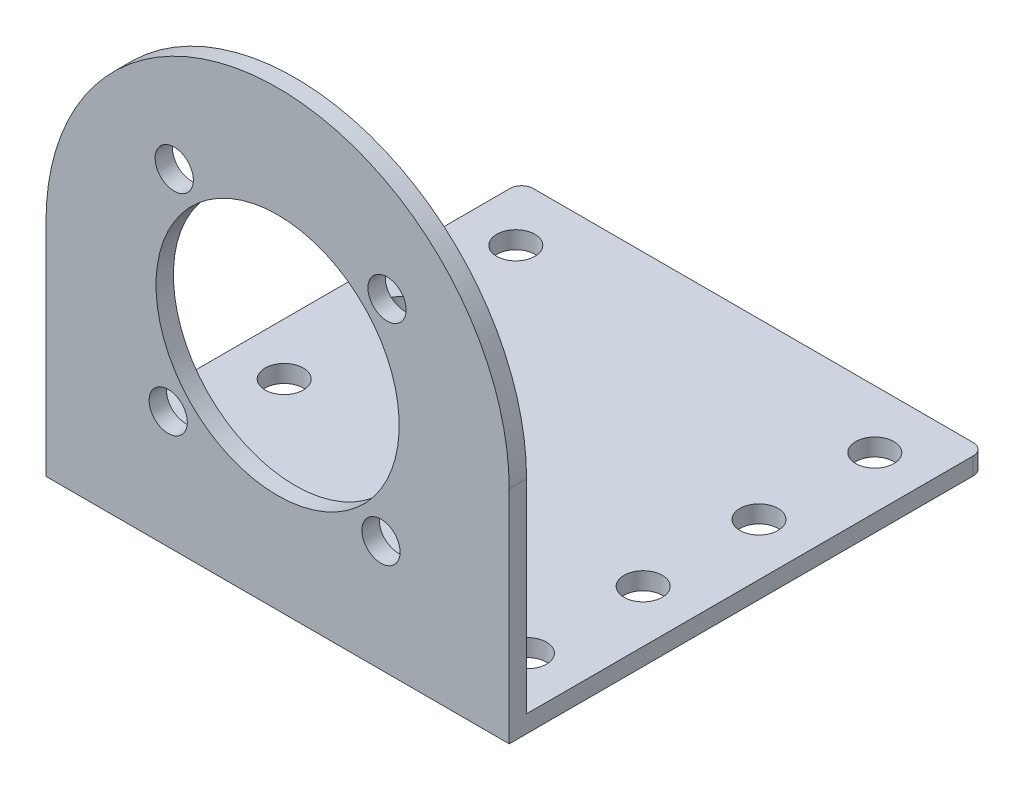
SolidWorks part; units mm, degrees
ref_plane "Front Plane" through (0, 0, 0) normal (0, 0, 1) x (1, 0, 0)
ref_plane "Top Plane" through (0, 0, 0) normal (0, 1, 0) x (1, 0, 0)
ref_plane "Right Plane" through (0, 0, 0) normal (1, 0, 0) x (0, 0, -1)
sketch "Sketch2" plane through (0, 0, 0) normal (1, 0, 0) x (0, 0, -1)
  line L1 (-36.8894, 36.5355) -> (-35.3894, 36.5355)
  line L2 (-36.8894, 36.5355) -> (-36.8894, -2.5345)
  line L3 (-36.8894, -2.5345) -> (-35.3894, -2.5345)
  line L4 (-35.3894, 36.5355) -> (-35.3894, -2.5345)
  line L5 (-36.8894, -2.5345) -> (4.1796, -2.5345)
  line L6 (-36.8894, -2.5345) -> (-36.8894, -1.0345)
  line L7 (-36.8894, -1.0345) -> (4.1796, -1.0345)
  line L8 (4.1796, -2.5345) -> (4.1796, -1.0345)
  dimension "D1" = 1.5
  dimension "D2" = 1.5
  dimension "D3" = 39.07
  dimension "D4" = 41.069
extrude "Boss-Extrude1" add sketch "Sketch2" along normal blind 40 contours L3 L4 L1 L2 | L5 L8 L7 L6
sketch "Sketch3" plane through (0, -1.0345, 0) normal (0, 1, 0) x (1, 0, 0)
  line L0 (40, 4.1796) -> (0, 4.1796) construction
  line L1 (0, -35.3894) -> (0, 4.1796) construction
  line L2 (40, -35.3894) -> (40, 4.1796) construction
  circle A0 centre (4.5, -30.8204) radius 1.65
  circle A1 centre (4.5, -20.8204) radius 1.65
  circle A2 centre (4.5, -10.8204) radius 1.65
  circle A3 centre (4.5, -0.8204) radius 1.65
  circle A4 centre (35.5, -30.8204) radius 1.65
  circle A5 centre (35.5, -20.8204) radius 1.65
  circle A6 centre (35.5, -10.8204) radius 1.65
  circle A7 centre (35.5, -0.8204) radius 1.65
  dimension "D1" = 3.3
  dimension "D2" = 5
  dimension "D3" = 10
  dimension "D4" = 10
  dimension "D5" = 10
  dimension "D6" = 5
  dimension "D7" = 10
  dimension "D8" = 10
  dimension "D9" = 30
  dimension "D10" = 4.5
  dimension "D11" = 4.5
  dimension "D12" = 4.5
  dimension "D13" = 4.5
  dimension "D14" = 4.5
  dimension "D15" = 4.5
extrude "Cut-Extrude1" cut sketch "Sketch3" against normal blind 40
sketch "Sketch4" plane through (0, 0, 35.3894) normal (0, 0, -1) x (-1, 0, 0)
  circle A0 centre (-20, 16.5355) radius 10.5
  circle A1 centre (-20, 16.5355) radius 13
  circle A2 centre (-29.4484, 25.4645) radius 1.65
  circle A3 centre (-10.5516, 7.6065) radius 1.65
  circle A4 centre (-28.929, 7.0871) radius 1.65
  circle A5 centre (-11.071, 25.984) radius 1.65
  arc A6 (-40, 16.5355) -> (0, 16.5355) centre (-20, 16.5355) cw
  line M2 (0, -1.0345) -> (0, 36.5355)
  line M3 (0, 36.5355) -> (-40, 36.5355)
  line M4 (-40, 36.5355) -> (-40, -1.0345)
  dimension "D1" = 21
  dimension "D4" = 26
  dimension "D5" = 3.3
  dimension "D9" = 20
  dimension "D2" = 19.07
  dimension "D3" = 20
  dimension "D6" = 90
  dimension "D7" = 90
  dimension "D8" = 90
  dimension "D10" = 40
extrude "Cut-Extrude2" cut sketch "Sketch4" against normal blind 40 contours A0 | A1 A4 | A1 A4 | A1 A3 | A1 A3 | A6 M4 M3 | A6 M3 M2 | A1 A5 | A1 A5 | A1 A2 | A1 A2
fillet "Fillet1" radius 1 2 edges at (0, -1.7845, -4.1796) (40, -1.7845, -4.1796)
